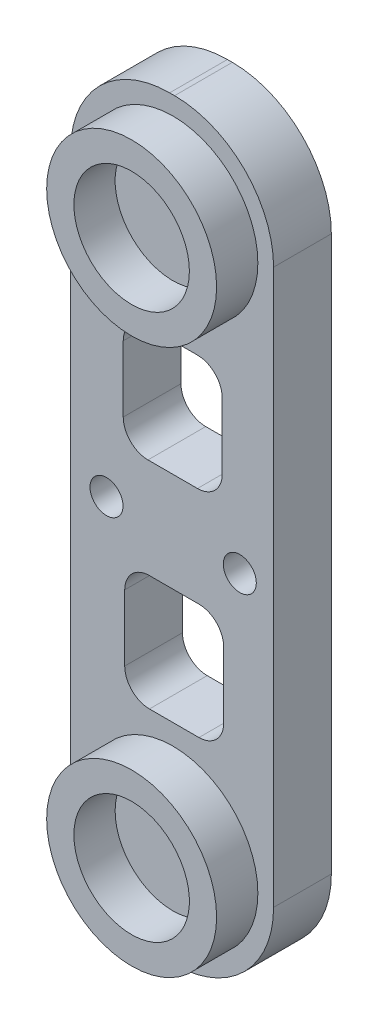
SolidWorks part; units mm, degrees
ref_plane "Front Plane" through (0, 0, 0) normal (0, 0, 1) x (1, 0, 0)
ref_plane "Top Plane" through (0, 0, 0) normal (0, 1, 0) x (1, 0, 0)
ref_plane "Right Plane" through (0, 0, 0) normal (1, 0, 0) x (0, 0, -1)
other "Graphic1"
other "object_1 (Open) -1"
ref_plane "Plane1" through (0, 0, 10) normal (0, 0, 1) x (1, 0, 0)
sketch "Sketch1" plane through (0, 0, 10) normal (0, 0, 1) x (1, 0, 0)
  line L1 (-301.228, 339.9252) -> (-288.928, 339.9252)
  line L2 (-301.228, 339.9252) -> (-301.228, 294.3252)
  line L3 (-301.228, 294.3252) -> (-288.928, 294.3252)
  line L4 (-288.928, 339.9252) -> (-288.928, 294.3252)
  line L5 (-291.9514, 306.9769) -> (-297.9514, 306.9769)
  line L6 (-291.9514, 306.9769) -> (-291.9514, 313.9769)
  line L7 (-291.9514, 313.9769) -> (-297.9514, 313.9769)
  line L8 (-297.9514, 306.9769) -> (-297.9514, 313.9769)
  line L9 (-292.0408, 320.0028) -> (-298.0408, 320.0028)
  line L10 (-292.0408, 320.0028) -> (-292.0408, 327.0028)
  line L11 (-292.0408, 327.0028) -> (-298.0408, 327.0028)
  line L12 (-298.0408, 320.0028) -> (-298.0408, 327.0028)
  circle A0 centre (-290.9753, 316.8223) radius 1
  circle A1 centre (-299.0535, 316.8223) radius 1
  point P12 (-292.0408, 320.0028)
  dimension "D3" = 6
  dimension "D1" = 12.3
  dimension "D2" = 45.6
  dimension "D4" = 7
  dimension "D5" = 6
  dimension "D6" = 7
extrude "Boss-Extrude1" add sketch "Sketch1" along normal blind 3.5
fillet "Fillet1" radius 6 4 edges at (-288.928, 339.9252, 11.75) (-301.228, 339.9252, 11.75) (-288.928, 294.3252, 11.75) (-301.228, 294.3252, 11.75)
fillet "Fillet2" radius 1.5 8 edges at (-297.9514, 306.9769, 11.75) (-291.9514, 306.9769, 11.75) (-291.9514, 313.9769, 11.75) (-297.9514, 313.9769, 11.75) (-298.0408, 327.0028, 11.75) (-292.0408, 320.0028, 11.75) (-298.0408, 320.0028, 11.75) (-292.0408, 327.0028, 11.75)
sketch "Sketch2" plane through (0, 0, 13.5) normal (0, 0, 1) x (1, 0, 0)
  line L0 (-288.928, 317.1252) -> (-280.0834, 317.1252) construction
  line L1 (-288.928, 300.3252) -> (-288.928, 333.9252) construction
  circle A0 centre (-295.0313, 333.6611) radius 3.5
  circle A1 centre (-295.0313, 333.6611) radius 5.15
  circle A2 centre (-295.0313, 300.5893) radius 5.15
  circle A3 centre (-295.0313, 300.5893) radius 3.5
extrude "Boss-Extrude2" add sketch "Sketch2" along normal blind 2.5
